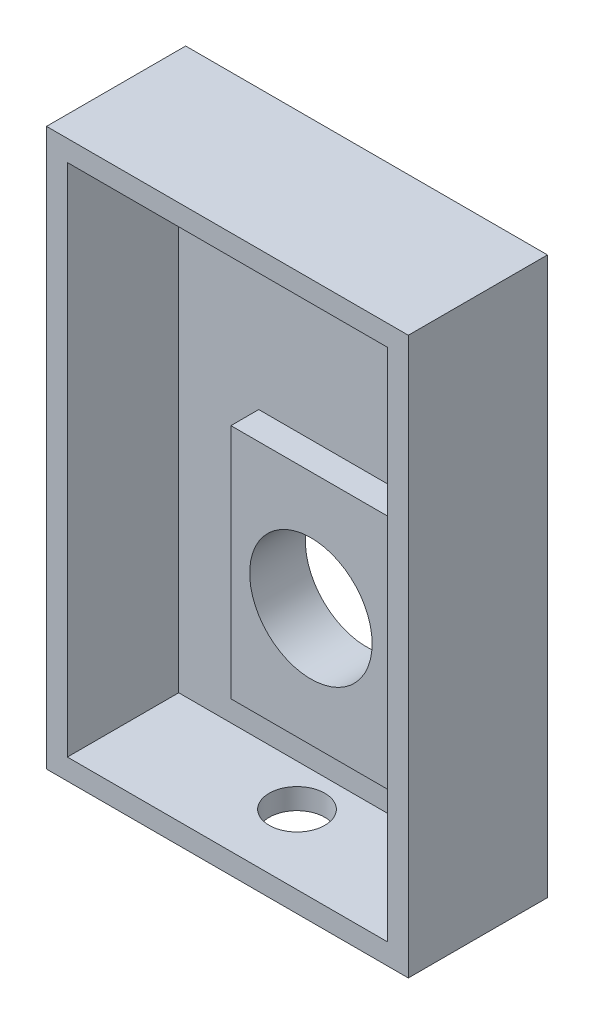
SolidWorks part; units mm, degrees
ref_plane "Front Plane" through (0, 0, 0) normal (0, 0, 1) x (1, 0, 0)
ref_plane "Top Plane" through (0, 0, 0) normal (0, 1, 0) x (1, 0, 0)
ref_plane "Right Plane" through (0, 0, 0) normal (1, 0, 0) x (0, 0, -1)
sketch "Sketch1" plane through (0, 0, 0) normal (0, 0, 1) x (1, 0, 0)
  line L1 (0, 0) -> (26, 0)
  line L2 (0, 0) -> (0, -40)
  line L3 (0, -40) -> (26, -40)
  line L4 (26, 0) -> (26, -40)
  line L5 (7.25, -18) -> (18.75, -18) construction
  line L6 (7.25, -18) -> (7.25, -35) construction
  line L7 (7.25, -35) -> (18.75, -35) construction
  line L8 (18.75, -18) -> (18.75, -35) construction
  circle A0 centre (13, -26.5) radius 4.4
  point P9 (13, -18)
  point P10 (13, 0)
  point P11 (18.75, -26.5)
  point P15 (0, 0)
  point P16 (0, 0)
  dimension "D5" = 8.8
  dimension "D1" = 40
  dimension "D2" = 26
  dimension "D3" = 11.5
  dimension "D4" = 17
  dimension "D6" = 18
extrude "Boss-Extrude1" add sketch "Sketch1" along normal blind 2
sketch "Sketch2" plane through (0, 0, 2) normal (0, 0, 1) x (1, 0, 0)
  line L0 (7.25, -18) -> (18.75, -18) construction
  line L1 (7.25, -18) -> (18.75, -18)
  line L2 (7.25, -18) -> (7.25, -35) construction
  line L3 (7.25, -18) -> (7.25, -35)
  line L4 (18.75, -18) -> (18.75, -35) construction
  line L5 (18.75, -18) -> (18.75, -35)
  line L6 (7.25, -35) -> (18.75, -35) construction
  line L7 (7.25, -35) -> (18.75, -35)
  circle A0 centre (13, -26.5) radius 4.4 construction
  circle A1 centre (13, -26.5) radius 4.4
extrude "Boss-Extrude2" add sketch "Sketch2" along normal blind 2
sketch "Sketch3" plane through (0, 0, 2) normal (0, 0, 1) x (1, 0, 0)
  line L0 (1.5, -1.5) -> (1.5, -38.5)
  line L1 (1.5, -38.5) -> (24.5, -38.5)
  line L2 (24.5, -38.5) -> (24.5, -1.5)
  line L3 (24.5, -1.5) -> (1.5, -1.5)
  line L4 (0, 0) -> (0, -40)
  line L5 (0, -40) -> (26, -40)
  line L6 (26, -40) -> (26, 0)
  line L7 (26, 0) -> (0, 0)
  line L8 (0, 0) -> (0, -40)
  line L9 (0, -40) -> (26, -40)
  line L10 (26, -40) -> (26, 0)
  line L11 (26, 0) -> (0, 0)
  dimension "D1" = 0
  dimension "D2" = 1.5
extrude "Boss-Extrude3" add sketch "Sketch3" along normal blind 8
sketch "Sketch4" plane through (0, -40, 0) normal (0, -1, 0) x (1, 0, 0)
  line L0 (26, 10) -> (26, 0) construction
  line L1 (0, 10) -> (26, 10) construction
  circle A0 centre (13, 5) radius 2
  point P2 (0, 0)
  point P5 (26, 5)
  point P6 (0, 0)
  point P9 (13, 10)
  dimension "D1" = 4
extrude "Cut-Extrude1" cut sketch "Sketch4" against normal blind 2
